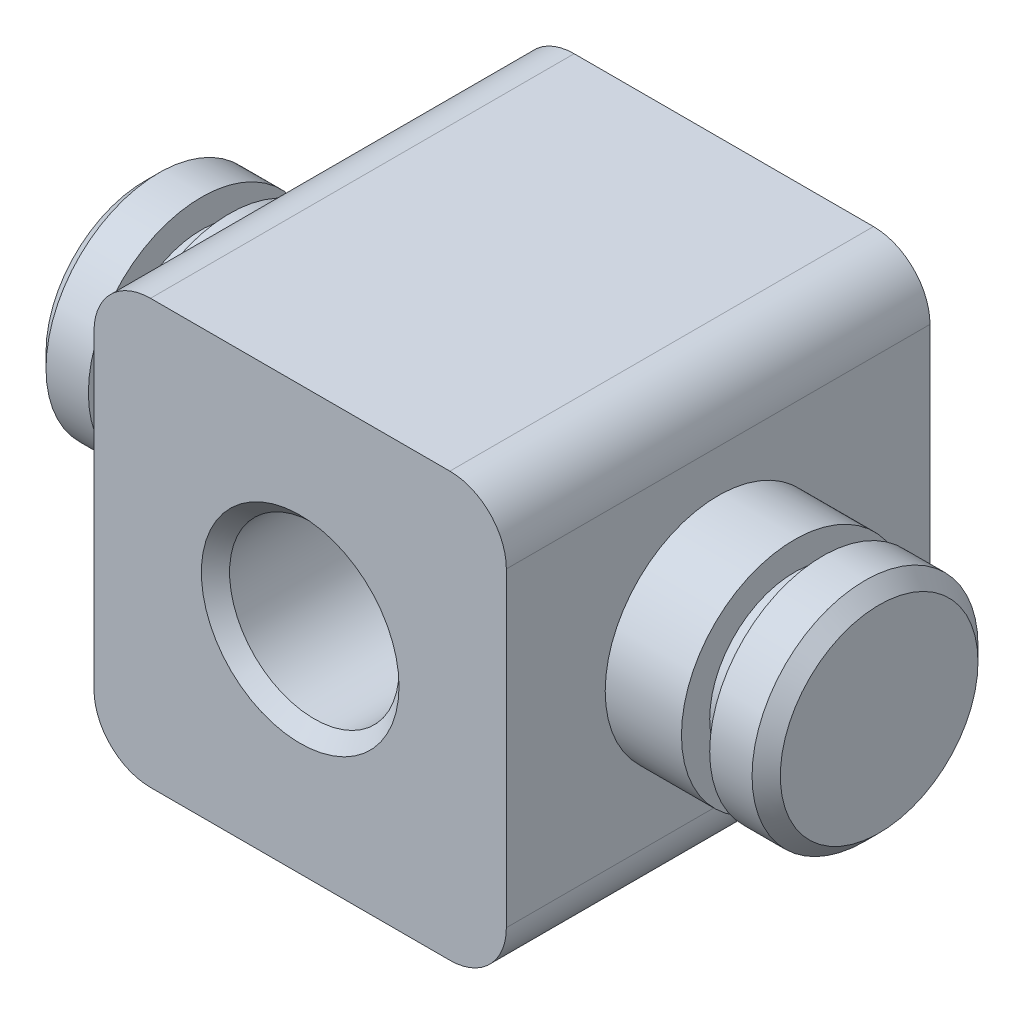
SolidWorks part; units mm, degrees
ref_plane "Front Plane" through (0, 0, 0) normal (0, 0, 1) x (1, 0, 0)
ref_plane "Top Plane" through (0, 0, 0) normal (0, 1, 0) x (1, 0, 0)
ref_plane "Right Plane" through (0, 0, 0) normal (1, 0, 0) x (0, 0, -1)
sketch "Sketch1" plane through (0, 0, 0) normal (0, 0, 1) x (1, 0, 0)
  line L1 (-5.3, -7.5) -> (5.3, -7.5)
  line L2 (-7.3, -5.5) -> (-7.3, 5.5)
  line L3 (-5.3, 7.5) -> (5.3, 7.5)
  line L4 (7.3, -5.5) -> (7.3, 5.5)
  line L5 (-7.3, -7.5) -> (7.3, 7.5) construction
  line L6 (-7.3, 7.5) -> (7.3, -7.5) construction
  circle A0 centre (0, 0) radius 3
  arc A1 (5.3, -7.5) -> (7.3, -5.5) centre (5.3, -5.5) ccw
  arc A2 (-5.3, -7.5) -> (-7.3, -5.5) centre (-5.3, -5.5) cw
  arc A3 (-7.3, 5.5) -> (-5.3, 7.5) centre (-5.3, 5.5) cw
  arc A4 (5.3, 7.5) -> (7.3, 5.5) centre (5.3, 5.5) cw
  point P0 (0, 0)
  dimension "D3" = 6
  dimension "D4" = 2
  dimension "D1" = 15
  dimension "D2" = 14.6
extrude "Boss-Extrude1" add sketch "Sketch1" along normal blind 15
sketch "Sketch2" plane through (-7.3, 0, 0) normal (-1, 0, 0) x (0, 0, 1)
  line L0 (15, 5.5) -> (15, -5.5) construction
  circle A0 centre (7.5, 0) radius 4
  dimension "D3" = 8
  dimension "D1" = 7.5
  dimension "D2" = 7.5
extrude "Boss-Extrude2" add sketch "Sketch2" along normal blind 2.7
sketch "Sketch3" plane through (-10, 0, 0) normal (-1, 0, 0) x (0, 0, 1)
  circle A0 centre (7.5, 0) radius 3
  dimension "D1" = 6
extrude "Boss-Extrude3" add sketch "Sketch3" along normal blind 1
sketch "Sketch4" plane through (-11, 0, 0) normal (-1, 0, 0) x (0, 0, 1)
  circle A0 centre (7.5, 0) radius 4
extrude "Boss-Extrude4" add sketch "Sketch4" along normal blind 2
chamfer "Chamfer1" distance 0.5 angle 45 1 edges at (-13, 0, 11.5)
mirror "Mirror1" about plane through (0, 0, 0) normal (1, 0, 0) of "Chamfer1", "Boss-Extrude4", "Boss-Extrude3", "Boss-Extrude2"
chamfer "Chamfer2" distance 0.5 angle 45 2 edges at (3, 0, 0) (3, 0, 15)
